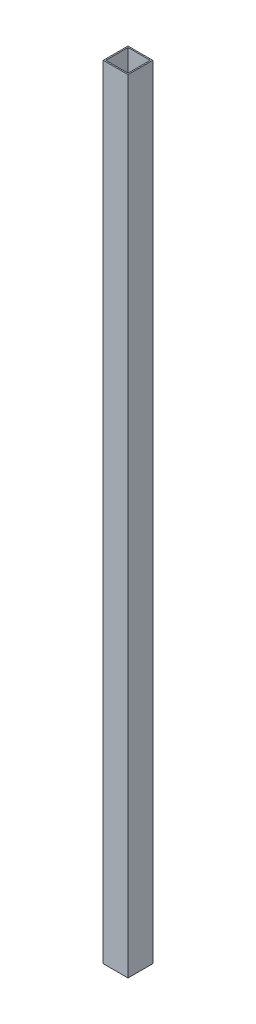
SolidWorks part; units mm, degrees
ref_plane "Front Plane" through (0, 0, 0) normal (0, 0, 1) x (1, 0, 0)
ref_plane "Top Plane" through (0, 0, 0) normal (0, 1, 0) x (1, 0, 0)
ref_plane "Right Plane" through (0, 0, 0) normal (1, 0, 0) x (0, 0, -1)
sketch "Sketch1" plane through (0, 0, 0) normal (0, 1, 0) x (1, 0, 0)
  line L1 (0, 0) -> (25.4, 0)
  line L2 (0, 0) -> (0, 25.4)
  line L3 (0, 25.4) -> (25.4, 25.4)
  line L4 (25.4, 0) -> (25.4, 25.4)
  dimension "D1" = 25.4
  dimension "D2" = 25.4
extrude "Boss-Extrude1" add sketch "Sketch1" along normal blind 802.767
sketch "Sketch3" plane through (0, 802.767, 0) normal (0, 1, 0) x (1, 0, 0)
  line L0 (25.4, 25.4) -> (0, 25.4) construction
  line L1 (24.13, 24.13) -> (1.27, 24.13)
  line L2 (24.13, 24.13) -> (24.13, 1.27)
  line L3 (24.13, 1.27) -> (1.27, 1.27)
  line L4 (1.27, 24.13) -> (1.27, 1.27)
  line L5 (25.4, 0) -> (25.4, 25.4) construction
  line L6 (0, 25.4) -> (0, 0) construction
  line L7 (0, 0) -> (25.4, 0) construction
  dimension "D1" = 1.27
  dimension "D2" = 1.27
  dimension "D3" = 1.27
  dimension "D4" = 1.27
extrude "Cut-Extrude1" cut sketch "Sketch3" against normal through all
